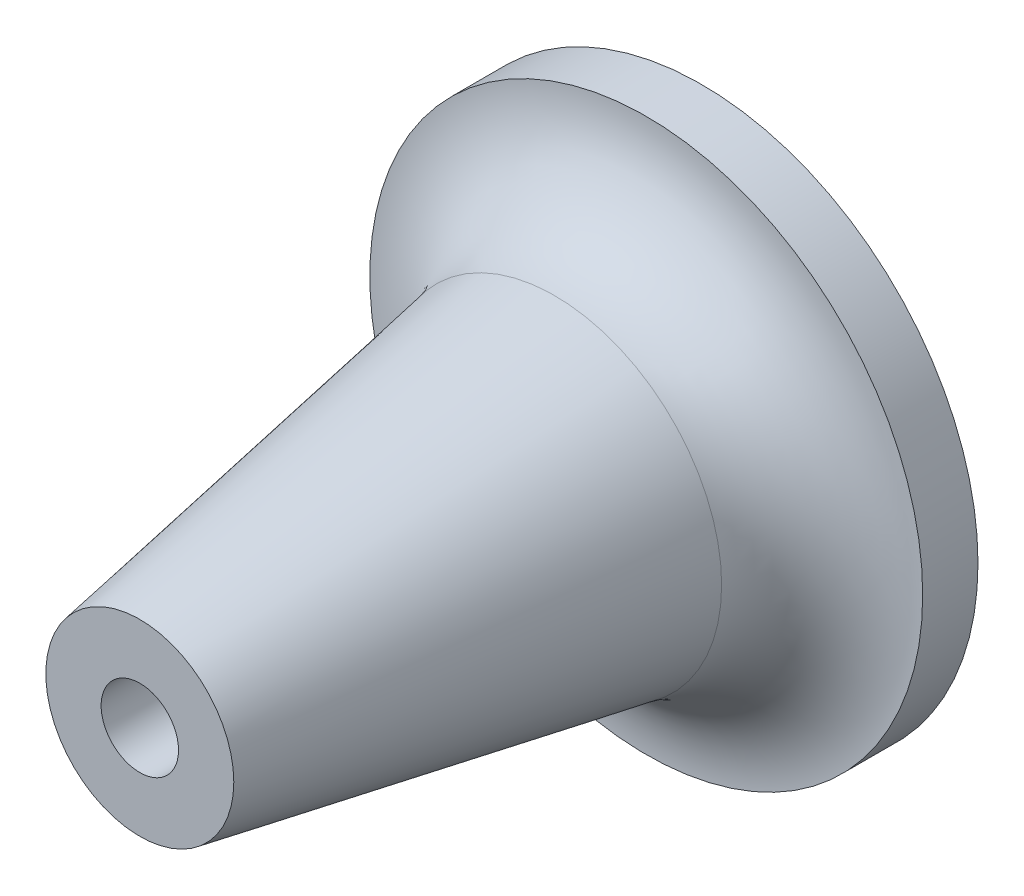
SolidWorks part; units mm, degrees
material "ABS"
ref_plane "Front Plane" through (0, 0, 0) normal (0, 0, 1) x (1, 0, 0)
ref_plane "Top Plane" through (0, 0, 0) normal (0, 1, 0) x (1, 0, 0)
ref_plane "Right Plane" through (0, 0, 0) normal (1, 0, 0) x (0, 0, -1)
sketch "Sketch1" plane through (0, 0, 0) normal (1, 0, 0) x (0, 0, -1)
  line L0 (-51.4955, 0) -> (51.4955, 0) construction
  line L1 (-33.7154, 3.5) -> (-28.7154, 3.5)
  line L2 (-33.7154, 8.5) -> (3.7884, 15.1129)
  line L3 (12.0846, 25) -> (17.0846, 25)
  line L5 (-33.7154, 8.5) -> (-33.7154, 3.5)
  line L6 (10.5846, 11.1) -> (17.0846, 11.1)
  line L7 (17.0846, 11.1) -> (17.0846, 25)
  line L11 (-28.7154, 3.5) -> (10.5846, 11.1)
  arc A0 (3.7884, 15.1129) -> (12.0846, 25) centre (2.045, 25) ccw
  dimension "D3" = 5
  dimension "D4" = 25
  dimension "D1" = 11.1
  dimension "D2" = 5
  dimension "D5" = 5
  dimension "D6" = 6.5
  dimension "D7" = 3.5
revolve "Revolve1" add sketch "Sketch1" angle 360 about L0
